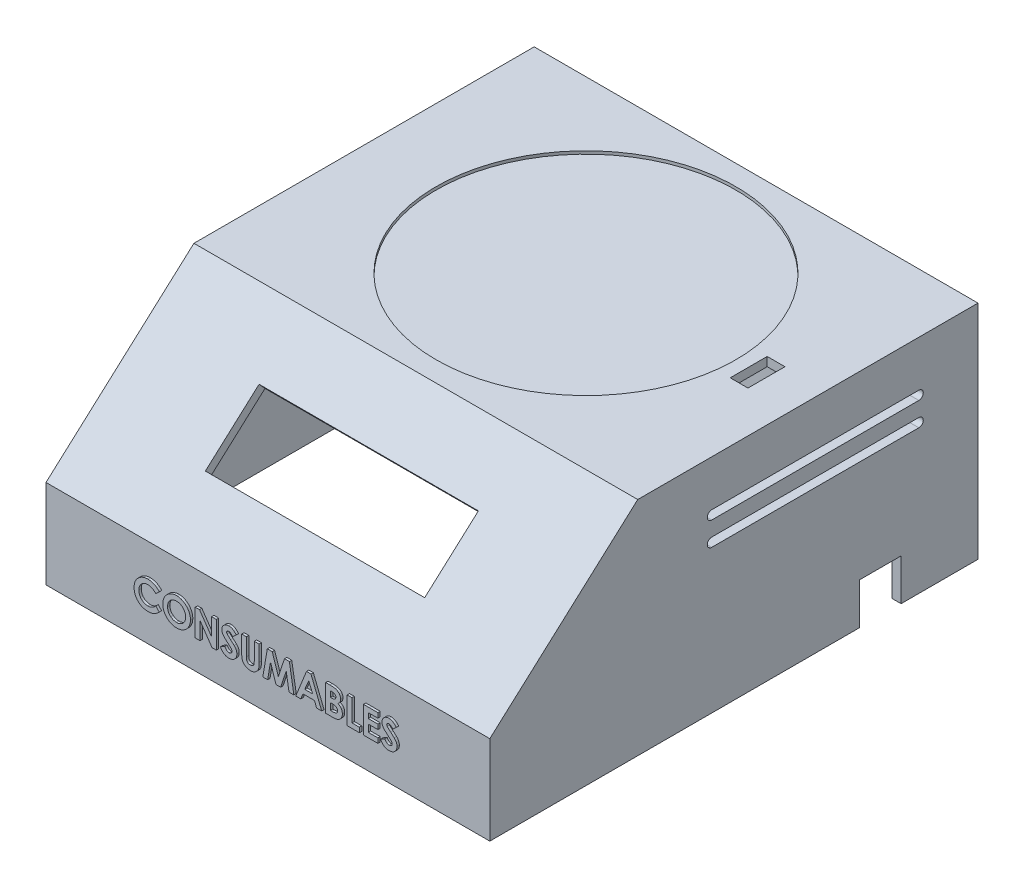
SolidWorks part; units mm, degrees
ref_plane "Front Plane" through (0, 0, 0) normal (0, 0, 1) x (1, 0, 0)
ref_plane "Top Plane" through (0, 0, 0) normal (0, 1, 0) x (1, 0, 0)
ref_plane "Right Plane" through (0, 0, 0) normal (1, 0, 0) x (0, 0, -1)
ref_plane "P1_Right_-75" through (-75, 0, 0) normal (1, 0, 0) x (0, 0, -1)
sketch "Sketch1" plane through (-75, 0, 0) normal (1, 0, 0) x (0, 0, -1)
  line L0 (0, 0) -> (-165, 0)
  line L1 (-165, 0) -> (-165, 30)
  line L2 (-165, 30) -> (-115, 75)
  line L3 (-115, 75) -> (0, 75)
  line L4 (0, 75) -> (0, 0)
extrude "Block" add sketch "Sketch1" along normal blind 150
shell "Shell1" thickness 3
sketch "Sketch2" plane through (0, 0, 0) normal (0, 1, 0) x (1, 0, 0)
  circle A0 centre (-68, -7) radius 5
  circle A1 centre (68, -7) radius 5
  circle A2 centre (-68, -158) radius 5
  circle A3 centre (68, -158) radius 5
extrude "Floor columns" add sketch "Sketch2" along normal blind 20
sketch "Sketch3" plane through (0, 0, 0) normal (0, 1, 0) x (1, 0, 0)
  circle A0 centre (-68, -7) radius 2
  circle A1 centre (68, -7) radius 2
  circle A2 centre (-68, -158) radius 2
  circle A3 centre (68, -158) radius 2
extrude "Floor insert holes" cut sketch "Sketch3" along normal blind 7
ref_plane "P2_Top_75" through (0, 75, 0) normal (0, 1, 0) x (1, 0, 0)
sketch "Sketch4" plane through (0, 75, 0) normal (0, 1, 0) x (1, 0, 0)
  circle A0 centre (0, -57.5) radius 50.675
extrude "Scale recess" cut sketch "Sketch4" against normal blind 1
sketch "Sketch5" plane through (0, 75, 0) normal (0, 1, 0) x (1, 0, 0)
  line L1 (55, -63.75) -> (61, -63.75)
  line L2 (55, -63.75) -> (55, -51.25)
  line L3 (55, -51.25) -> (61, -51.25)
  line L4 (61, -63.75) -> (61, -51.25)
  line L5 (55, -63.75) -> (61, -51.25) construction
  line L6 (55, -51.25) -> (61, -63.75) construction
  point P0 (58, -57.5)
extrude "Load-cell cable slot" cut sketch "Sketch5" against normal blind 4
sketch "Sketch6" plane through (0, 98.6188, 88.7569) normal (0, 0.7433, 0.669) x (1, 0, 0)
  line L0 (-37.065, -81.1505) -> (37.065, -81.1505)
  line L1 (37.065, -81.1505) -> (37.065, -56.7305)
  line L2 (37.065, -56.7305) -> (-37.065, -56.7305)
  line L3 (-37.065, -56.7305) -> (-37.065, -81.1505)
extrude "LCD window" cut sketch "Sketch6" against normal blind 4
sketch "Sketch7" plane through (0, 96.3889, 86.75) normal (0, -0.7433, -0.669) x (1, 0, 0)
  circle A0 centre (-37.5, 84.4405) radius 2.5
  circle A1 centre (-37.5, 53.4405) radius 2.5
  circle A2 centre (37.5, 84.4405) radius 2.5
  circle A3 centre (37.5, 53.4405) radius 2.5
extrude "LCD bosses" add sketch "Sketch7" along normal blind 5.6
sketch "Sketch8" plane through (0, 92.2265, 83.0038) normal (0, -0.7433, -0.669) x (1, 0, 0)
  circle A0 centre (-37.5, 84.4405) radius 1.1
  circle A1 centre (-37.5, 53.4405) radius 1.1
  circle A2 centre (37.5, 84.4405) radius 1.1
  circle A3 centre (37.5, 53.4405) radius 1.1
extrude "LCD M2.5 pilots" cut sketch "Sketch8" against normal blind 7.6
ref_plane "P3_Right_75" through (75, 0, 0) normal (1, 0, 0) x (0, 0, -1)
sketch "Sketch9" plane through (75, 0, 0) normal (1, 0, 0) x (0, 0, -1)
  line L1 (-40, 0) -> (-26, 0)
  line L2 (-40, 0) -> (-40, 14)
  line L3 (-40, 14) -> (-26, 14)
  line L4 (-26, 0) -> (-26, 14)
  line L5 (-40, 0) -> (-26, 14) construction
  line L6 (-40, 14) -> (-26, 0) construction
  point P0 (-33, 7)
extrude "USB access" cut sketch "Sketch9" against normal blind 4
sketch "Sketch10" plane through (0, 0, 0) normal (0, 0, 1) x (1, 0, 0)
  circle A0 centre (-38, 45) radius 8.15
extrude "DC in" cut sketch "Sketch10" along normal blind 4
ref_plane "P4_Right_-75" through (-75, 0, 0) normal (1, 0, 0) x (0, 0, -1)
sketch "Sketch11" plane through (-75, 0, 0) normal (1, 0, 0) x (0, 0, -1)
  line L0 (-20, 50) -> (-90, 50) construction
  line L1 (-20, 48.5) -> (-90, 48.5)
  line L2 (-20, 51.5) -> (-90, 51.5)
  line L3 (-20, 58) -> (-90, 58) construction
  line L4 (-20, 56.5) -> (-90, 56.5)
  line L5 (-20, 59.5) -> (-90, 59.5)
  arc A0 (-20, 48.5) -> (-20, 51.5) centre (-20, 50) ccw
  arc A1 (-90, 51.5) -> (-90, 48.5) centre (-90, 50) ccw
  arc A2 (-20, 56.5) -> (-20, 59.5) centre (-20, 58) ccw
  arc A3 (-90, 59.5) -> (-90, 56.5) centre (-90, 58) ccw
  point P2 (-55, 50)
  point P7 (-55, 58)
  point P14 (0, 0)
extrude "Vents left" cut sketch "Sketch11" along normal blind 4
ref_plane "P5_Right_75" through (75, 0, 0) normal (1, 0, 0) x (0, 0, -1)
sketch "Sketch12" plane through (75, 0, 0) normal (1, 0, 0) x (0, 0, -1)
  line L0 (-20, 50) -> (-90, 50) construction
  line L1 (-20, 48.5) -> (-90, 48.5)
  line L2 (-20, 51.5) -> (-90, 51.5)
  line L3 (-20, 58) -> (-90, 58) construction
  line L4 (-20, 56.5) -> (-90, 56.5)
  line L5 (-20, 59.5) -> (-90, 59.5)
  arc A0 (-20, 48.5) -> (-20, 51.5) centre (-20, 50) ccw
  arc A1 (-90, 51.5) -> (-90, 48.5) centre (-90, 50) ccw
  arc A2 (-20, 56.5) -> (-20, 59.5) centre (-20, 58) ccw
  arc A3 (-90, 59.5) -> (-90, 56.5) centre (-90, 58) ccw
  point P2 (-55, 50)
  point P7 (-55, 58)
  point P14 (0, 0)
extrude "Vents right" cut sketch "Sketch12" against normal blind 4
ref_plane "P6_Front_165" through (0, 0, 165) normal (0, 0, 1) x (1, 0, 0)
sketch "Sketch13" plane through (0, 0, 165) normal (0, 0, 1) x (1, 0, 0)
  text T0 "CONSUMABLES" font "Century Gothic" height 9
extrude "Title (raised)" add sketch "Sketch13" along normal blind 0.8
